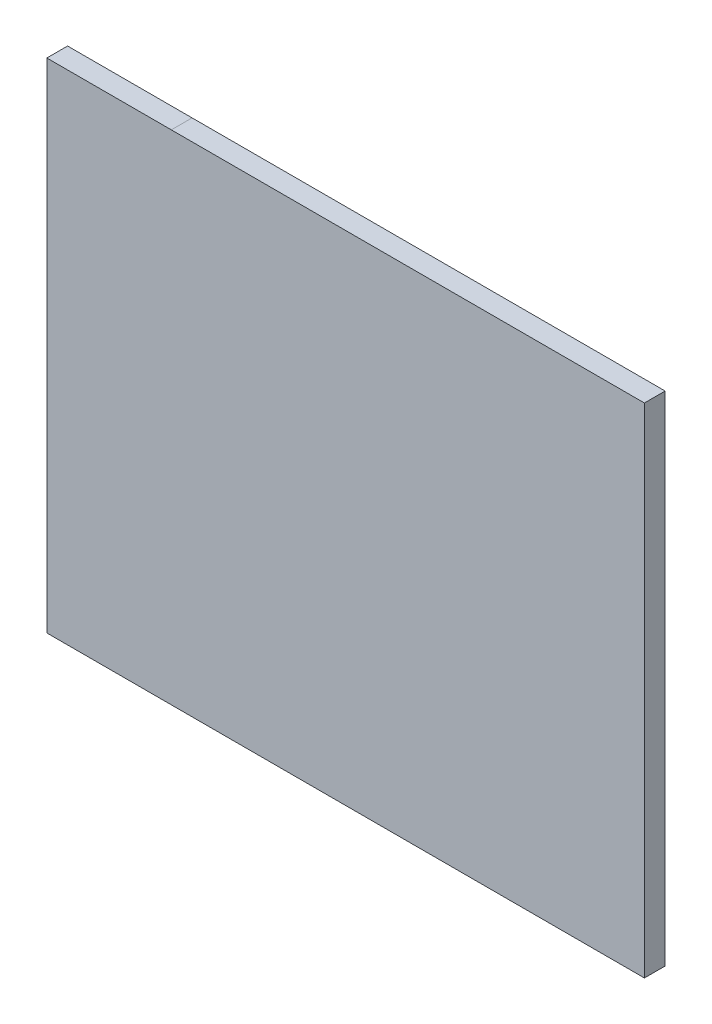
SolidWorks part; units mm, degrees
ref_plane "Front" through (0, 0, 0) normal (0, 0, 1) x (1, 0, 0)
ref_plane "Top" through (0, 0, 0) normal (0, 1, 0) x (1, 0, 0)
ref_plane "Right" through (0, 0, 0) normal (1, 0, 0) x (0, 0, -1)
other "Configuration Table"
sketch "Sketch1" plane through (0, 0, 0) normal (0, 0, 1) x (1, 0, 0)
  line L1 (0, -5994.4) -> (7315.2, -5994.4)
  line L2 (0, -5994.4) -> (0, 101.6)
  line L3 (0, 101.6) -> (7315.2, 101.6)
  line L4 (7315.2, -5994.4) -> (7315.2, 101.6)
  dimension "D1" = 7315.2
  dimension "D2" = 6096
extrude "Extrude1" add sketch "Sketch1" along normal blind 254
sketch "Sketch2" plane through (0, 101.6, 0) normal (0, 1, 0) x (-1, 0, 0)
  line L0 (-1524, -1803.4) -> (-1524, 4029.9149)
  line L1 (0, 254) -> (0, 0) construction
  dimension "D1" = 1524
split line "Split Line1"
